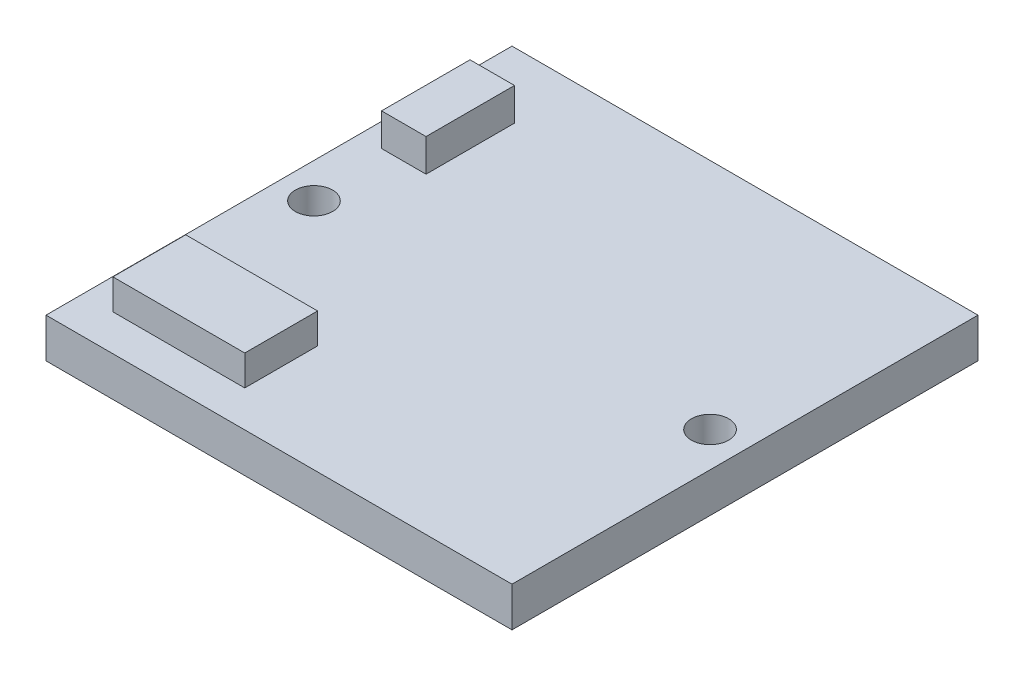
SolidWorks part; units mm, degrees
ref_plane "정면" through (0, 0, 0) normal (0, 0, 1) x (1, 0, 0)
ref_plane "윗면" through (0, 0, 0) normal (0, 1, 0) x (1, 0, 0)
ref_plane "우측면" through (0, 0, 0) normal (1, 0, 0) x (0, 0, -1)
sketch "스케치1" plane through (0, 0, 0) normal (0, 1, 0) x (1, 0, 0)
  line L1 (0, 0) -> (20, 0)
  line L2 (0, 0) -> (0, 20)
  line L3 (0, 20) -> (20, 20)
  line L4 (20, 0) -> (20, 20)
  dimension "D1" = 20
  dimension "D2" = 20
extrude "보스-돌출1" add sketch "스케치1" along normal blind 1.7
sketch "스케치2" plane through (0, 0, 0) normal (0, 1, 0) x (1, 0, 0)
  line L0 (0, 0) -> (20, 0) construction
  line L1 (2.03, 3.5) -> (2.73, 3.5)
  line L2 (2.03, 3.5) -> (2.03, 2)
  line L3 (2.03, 2) -> (2.73, 2)
  line L4 (2.73, 3.5) -> (2.73, 2)
  line L5 (0, 20) -> (0, 0) construction
  line L6 (3.3, 3.5) -> (4, 3.5)
  line L7 (3.3, 3.5) -> (3.3, 2)
  line L8 (3.3, 2) -> (4, 2)
  line L9 (4, 3.5) -> (4, 2)
  line L10 (4.57, 3.5) -> (5.27, 3.5)
  line L11 (4.57, 3.5) -> (4.57, 2)
  line L12 (4.57, 2) -> (5.27, 2)
  line L13 (5.27, 3.5) -> (5.27, 2)
  line L14 (5.84, 3.5) -> (6.54, 3.5)
  line L15 (5.84, 3.5) -> (5.84, 2)
  line L16 (5.84, 2) -> (6.54, 2)
  line L17 (6.54, 3.5) -> (6.54, 2)
  line L18 (7.11, 3.5) -> (7.81, 3.5)
  line L19 (7.11, 3.5) -> (7.11, 2)
  line L20 (7.11, 2) -> (7.81, 2)
  line L21 (7.81, 3.5) -> (7.81, 2)
  line L22 (8.38, 3.5) -> (9.08, 3.5)
  line L23 (8.38, 3.5) -> (8.38, 2)
  line L24 (8.38, 2) -> (9.08, 2)
  line L25 (9.08, 3.5) -> (9.08, 2)
  line L26 (9.65, 3.5) -> (10.35, 3.5)
  line L27 (9.65, 3.5) -> (9.65, 2)
  line L28 (9.65, 2) -> (10.35, 2)
  line L29 (10.35, 3.5) -> (10.35, 2)
  line L30 (10.92, 3.5) -> (11.62, 3.5)
  line L31 (10.92, 3.5) -> (10.92, 2)
  line L32 (10.92, 2) -> (11.62, 2)
  line L33 (11.62, 3.5) -> (11.62, 2)
  line L34 (12.19, 3.5) -> (12.89, 3.5)
  line L35 (12.19, 3.5) -> (12.19, 2)
  line L36 (12.19, 2) -> (12.89, 2)
  line L37 (12.89, 3.5) -> (12.89, 2)
  line L38 (13.46, 3.5) -> (14.16, 3.5)
  line L39 (13.46, 3.5) -> (13.46, 2)
  line L40 (13.46, 2) -> (14.16, 2)
  line L41 (14.16, 3.5) -> (14.16, 2)
  line L42 (14.73, 3.5) -> (15.43, 3.5)
  line L43 (14.73, 3.5) -> (14.73, 2)
  line L44 (14.73, 2) -> (15.43, 2)
  line L45 (15.43, 3.5) -> (15.43, 2)
  line L46 (16, 3.5) -> (16.7, 3.5)
  line L47 (16, 3.5) -> (16, 2)
  line L48 (16, 2) -> (16.7, 2)
  line L49 (16.7, 3.5) -> (16.7, 2)
  line L50 (17.27, 3.5) -> (17.97, 3.5)
  line L51 (17.27, 3.5) -> (17.27, 2)
  line L52 (17.27, 2) -> (17.97, 2)
  line L53 (17.97, 3.5) -> (17.97, 2)
  dimension "D1" = 1.5
  dimension "D3" = 2
  dimension "D2" = 0.7
  dimension "D4" = 2.03
  dimension "D5" = 13
extrude "컷-돌출1" cut sketch "스케치2" along normal blind 0.05
sketch "스케치3" plane through (0, 1.7, 0) normal (0, 1, 0) x (1, 0, 0)
  line L0 (0, 20) -> (0, 0) construction
  line L1 (0, 0) -> (20, 0) construction
  line L2 (20, 0) -> (20, 20) construction
  circle A0 centre (1.5, 10) radius 0.8
  circle A1 centre (18.5, 10) radius 0.8
  dimension "D1" = 1.6
  dimension "D2" = 1.5
  dimension "D3" = 10
  dimension "D4" = 1.5
extrude "컷-돌출2" cut sketch "스케치3" against normal through all
sketch "스케치4" [suppressed] plane through (0, 1.6, 0) normal (0, 1, 0) x (1, 0, 0)
  line L1 (5.5914, 14.668) -> (9.5914, 14.668)
  line L2 (5.5914, 14.668) -> (5.5914, 10.668)
  line L3 (5.5914, 10.668) -> (9.5914, 10.668)
  line L4 (9.5914, 14.668) -> (9.5914, 10.668)
  line L5 (5.2619, 9.0782) -> (8.2619, 9.0782)
  line L6 (5.2619, 9.0782) -> (5.2619, 6.0782)
  line L7 (5.2619, 6.0782) -> (8.2619, 6.0782)
  line L8 (8.2619, 9.0782) -> (8.2619, 6.0782)
  line L9 (10.0846, 9.5813) -> (14.0846, 9.5813)
  line L10 (10.0846, 9.5813) -> (10.0846, 5.5813)
  line L11 (10.0846, 5.5813) -> (14.0846, 5.5813)
  line L12 (14.0846, 9.5813) -> (14.0846, 5.5813)
  line L13 (11.5509, 10.799) -> (14.5509, 10.799)
  line L14 (11.5509, 10.799) -> (11.5509, 15.799)
  line L15 (11.5509, 15.799) -> (14.5509, 15.799)
  line L16 (14.5509, 10.799) -> (14.5509, 15.799)
  dimension "D1" = 4
  dimension "D2" = 4
  dimension "D3" = 3
  dimension "D4" = 3
  dimension "D5" = 4
  dimension "D6" = 4
  dimension "D7" = 5
  dimension "D8" = 3
sketch "스케치5" plane through (0, 1.7, 0) normal (0, 1, 0) x (1, 0, 0)
  line L1 (3.5313, 18.6573) -> (7.4651, 18.6573)
  line L2 (3.5313, 18.6573) -> (3.5313, 16.6073)
  line L3 (3.5313, 16.6073) -> (7.4651, 16.6073)
  line L4 (7.4651, 18.6573) -> (7.4651, 16.6073)
  line L5 (0.9548, 12.5626) -> (4.7502, 12.5626)
  line L6 (0.9548, 12.5626) -> (0.9548, 14.4187)
  line L7 (0.9548, 14.4187) -> (4.7502, 14.4187)
  line L8 (4.7502, 12.5626) -> (4.7502, 14.4187)
  line L9 (0.9271, 1.0657) -> (2.811, 1.0657)
  line L10 (0.9271, 1.0657) -> (0.9271, 4.8056)
  line L11 (0.9271, 4.8056) -> (2.811, 4.8056)
  line L12 (2.811, 1.0657) -> (2.811, 4.8056)
  line L13 (3.365, 4.8056) -> (5.332, 4.8056)
  line L14 (3.365, 4.8056) -> (3.365, 1.0657)
  line L15 (3.365, 1.0657) -> (5.332, 1.0657)
  line L16 (5.332, 4.8056) -> (5.332, 1.0657)
  line L17 (14.8619, 4.1684) -> (18.9897, 4.1684)
  line L18 (14.8619, 4.1684) -> (14.8619, 2.1184)
  line L19 (14.8619, 2.1184) -> (18.9897, 2.1184)
  line L20 (18.9897, 4.1684) -> (18.9897, 2.1184)
extrude "보스-돌출2" [suppressed] add sketch "스케치5" along normal blind 1.8
sketch "스케치6" plane through (0, 1.7, 0) normal (0, 1, 0) x (1, 0, 0)
  line L1 (1.313, 4.6839) -> (6.9726, 4.6839)
  line L2 (1.313, 4.6839) -> (1.313, 1.558)
  line L3 (1.313, 1.558) -> (6.9726, 1.558)
  line L4 (6.9726, 4.6839) -> (6.9726, 1.558)
extrude "보스-돌출4" add sketch "스케치6" along normal blind 1.3
sketch "스케치7" plane through (0, 1.7, 0) normal (0, 1, 0) x (1, 0, 0)
  line L1 (1.0078, 13.3934) -> (2.9173, 13.3934)
  line L2 (1.0078, 13.3934) -> (1.0078, 17.1898)
  line L3 (1.0078, 17.1898) -> (2.9173, 17.1898)
  line L4 (2.9173, 13.3934) -> (2.9173, 17.1898)
extrude "보스-돌출5" add sketch "스케치7" along normal blind 1.4
equation "\"D4@스케치2\"=(20-(1.27*12+\"D2@스케치2\"))/2"
equation "\"D4@스케치3\"=\"D2@스케치3\""
